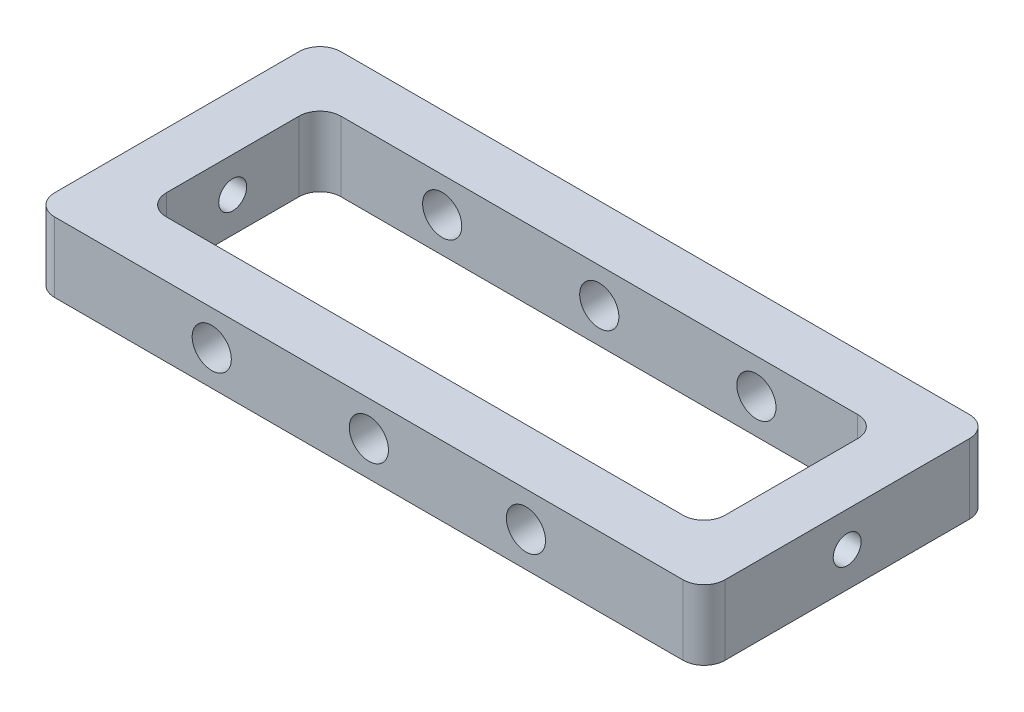
SolidWorks part; units mm, degrees
material "7079 Alloy"
ref_plane "Front Plane" through (0, 0, 0) normal (0, 0, 1) x (1, 0, 0)
ref_plane "Top Plane" through (0, 0, 0) normal (0, 1, 0) x (1, 0, 0)
ref_plane "Right Plane" through (0, 0, 0) normal (1, 0, 0) x (0, 0, -1)
sketch "Sketch1" plane through (0, 0, 0) normal (0, 1, 0) x (1, 0, 0)
  line L0 (-48, 3.2381) -> (-40, 3.2381) construction
  line L1 (-48, -20.5) -> (48, -20.5)
  line L2 (-48, -20.5) -> (-48, 20.5)
  line L3 (-48, 20.5) -> (48, 20.5)
  line L4 (48, -20.5) -> (48, 20.5)
  line L5 (-48, -20.5) -> (48, 20.5) construction
  line L6 (-48, 20.5) -> (48, -20.5) construction
  line L7 (-40, -12.5) -> (40, -12.5)
  line L8 (-40, -12.5) -> (-40, 12.5)
  line L9 (-40, 12.5) -> (40, 12.5)
  line L10 (40, -12.5) -> (40, 12.5)
  line L11 (-40, -12.5) -> (40, 12.5) construction
  line L12 (-40, 12.5) -> (40, -12.5) construction
  line L13 (40, 3.2381) -> (48, 3.2381) construction
  line L14 (-33.3216, 12.5) -> (-33.3216, 20.5) construction
  point P0 (0, 0)
  point P6 (0, 0)
  dimension "D1" = 96
  dimension "D2" = 80
  dimension "D3" = 41
extrude "Boss-Extrude1" add sketch "Sketch1" along normal blind 10
fillet "Fillet1" radius 3 4 edges at (48, 5, 20.5) (48, 5, -20.5) (-48, 5, 20.5) (-48, 5, -20.5)
sketch "Sketch2" plane through (-48, 0, 0) normal (-1, 0, 0) x (0, 0, 1)
  line L0 (-17.5, 5) -> (17.5, 5) construction
  line L1 (-17.5, 10) -> (-17.5, 0) construction
  line L2 (17.5, 0) -> (17.5, 10) construction
  circle A0 centre (0, 5) radius 2
extrude "Cut-Extrude1" cut sketch "Sketch2" against normal through all
sketch "Sketch3" plane through (0, 0, 20.5) normal (0, 0, 1) x (1, 0, 0)
  line L0 (-45, 5) -> (45, 5) construction
  line L1 (-45, 10) -> (-45, 0) construction
  line L2 (45, 0) -> (45, 10) construction
  line L3 (-45, 5) -> (-25.3043, 5) construction
  circle A0 centre (-22.5, 5) radius 2.8043
  circle A1 centre (0, 5) radius 2.8043
  circle A2 centre (22.5, 5) radius 2.8043
  dimension "D1" = 22.5
  dimension "D2" = 45
  dimension "D3" = 22.5
extrude "Cut-Extrude5" cut sketch "Sketch3" against normal through all contours A2 | A0 | A1
fillet "Fillet2" radius 3 4 edges at (-40, 5, 12.5) (40, 5, 12.5) (40, 5, -12.5) (-40, 5, -12.5)
